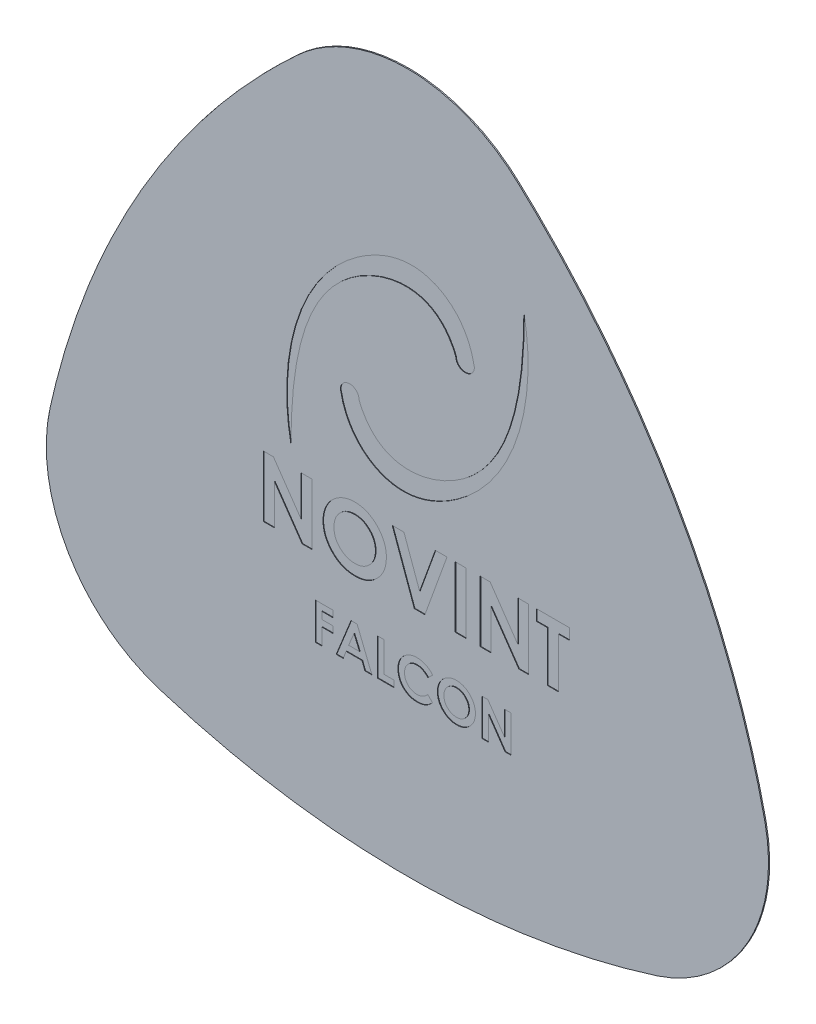
SolidWorks part; units mm, degrees
ref_plane "Plan de face" through (0, 0, 0) normal (0, 0, 1) x (1, 0, 0)
ref_plane "Plan de dessus" through (0, 0, 0) normal (0, 1, 0) x (1, 0, 0)
ref_plane "Plan de droite" through (0, 0, 0) normal (1, 0, 0) x (0, 0, -1)
sketch "Esquisse1" plane through (0, 0, 0) normal (0, 0, 1) x (1, 0, 0)
  spline S1 degree 3 poles (0, 149.25) (-0.1919, 149.25) (-0.4824, 149.2433) (-0.8671, 149.2249) (-1.227, 149.1976) (-1.4757, 149.1726) (-2.3358, 149.0732) (-3.7825, 148.7898) (-5.8615, 148.0277) (-7.7866, 146.9536) (-8.9312, 146.0552) (-11.3317, 143.854) (-14.9023, 140.2132) (-19.6452, 134.2118) (-23.6946, 127.7866) (-25.8978, 123.3061) (-27.3362, 119.9581) (-28.1637, 117.8887) (-29.2237, 114.8517) (-30.1569, 111.7368) (-30.7179, 109.4995) (-31.1222, 107.6788) (-31.3307, 106.3612) (-31.3402, 104.0862) (-30.9316, 101.6832) (-30.3995, 100.201) (-29.6911, 98.6209) (-28.6528, 96.8267) (-26.4804, 94.5101) (-23.992, 92.8324) (-22.3292, 92.1495) (-18.9808, 91.0951) (-13.9201, 89.8123) (-6.4025, 88.7423) (1.0481, 88.4673) (5.9721, 88.7938) (9.5908, 89.2221) (11.7967, 89.5402) (14.9568, 90.1407) (18.121, 90.89) (20.339, 91.5228) (22.118, 92.083) (23.3633, 92.5612) (25.3382, 93.6905) (27.215, 95.2458) (28.2326, 96.4478) (29.2467, 97.8513) (30.2814, 99.6476) (31.2015, 102.6873) (31.4102, 105.6811) (31.1702, 107.4626) (30.4092, 110.8896) (28.9898, 115.9137) (26.1576, 122.9592) (22.6705, 129.5491) (19.9257, 133.6501) (17.7454, 136.5698) (16.3935, 138.2864) (14.353, 140.661) (12.1535, 143.0027) (10.4653, 144.6485) (9.0029, 145.9895) (8.1968, 146.6474) (6.7793, 147.5233) (5.532, 148.1378) (4.1307, 148.6556) (2.6685, 149.0197) (1.2601, 149.2151) (0.4041, 149.25) (0, 149.25) (-0.1919, 149.25) (-0.4824, 149.2433) knots -0.004472 0 0 0 0.002123 0.004246 0.006369 0.008493 0.008493 0.020144 0.031796 0.043448 0.0551 0.0551 0.096159 0.137217 0.178275 0.219334 0.219334 0.238889 0.258444 0.277999 0.297554 0.297554 0.307313 0.317071 0.326829 0.336587 0.336587 0.349549 0.36251 0.375472 0.388433 0.388433 0.429492 0.47055 0.511609 0.552667 0.552667 0.572222 0.591777 0.611333 0.630888 0.630888 0.640646 0.650404 0.660162 0.66992 0.66992 0.682882 0.695844 0.708805 0.721767 0.721767 0.762825 0.803884 0.844942 0.886 0.886 0.905556 0.925111 0.944666 0.964221 0.964221 0.973166 0.977638 0.982111 0.986583 0.991055 0.995528 1 1 1 1.002123 1.004246 1.006369 only from (0, 149.25) to (0, 149.25)
extrude "Boss.-Extru.1" add sketch "Esquisse1" along normal blind 0.1
sketch "Esquisse2" plane through (0, 0, 0.1) normal (0, 0, 1) x (1, 0, 0)
  line L0 (-13.0847, 108.9955) -> (14.3157, 108.9955) construction
  line L1 (-8.3489, 102.1759) -> (11.1625, 102.1759) construction
  line L2 (0, 149.25) -> (0, 107.1447) construction
  arc A0 (4.1921, 129.7302) -> (5.8103, 129.7302) centre (5.0012, 129.7302) ccw
  arc A1 (-4.1921, 122.2698) -> (-5.8103, 122.2698) centre (-5.0012, 122.2698) ccw
  spline S0 degree 3 poles (0, 149.25) (-0.1919, 149.25) (-0.4824, 149.2433) (-0.8671, 149.2249) (-1.227, 149.1976) (-1.4757, 149.1726) (-2.3358, 149.0732) (-3.7825, 148.7898) (-5.8615, 148.0277) (-7.7866, 146.9536) (-8.9312, 146.0552) (-11.3317, 143.854) (-14.9023, 140.2132) (-19.6452, 134.2118) (-23.6946, 127.7866) (-25.8978, 123.3061) (-27.3362, 119.9581) (-28.1637, 117.8887) (-29.2237, 114.8517) (-30.1569, 111.7368) (-30.7179, 109.4995) (-31.1222, 107.6788) (-31.3307, 106.3612) (-31.3402, 104.0862) (-30.9316, 101.6832) (-30.3995, 100.201) (-29.6911, 98.6209) (-28.6528, 96.8267) (-26.4804, 94.5101) (-23.992, 92.8324) (-22.3292, 92.1495) (-18.9808, 91.0951) (-13.9201, 89.8123) (-6.4025, 88.7423) (1.0481, 88.4673) (5.9721, 88.7938) (9.5908, 89.2221) (11.7967, 89.5402) (14.9568, 90.1407) (18.121, 90.89) (20.339, 91.5228) (22.118, 92.083) (23.3633, 92.5612) (25.3382, 93.6905) (27.215, 95.2458) (28.2326, 96.4478) (29.2467, 97.8513) (30.2814, 99.6476) (31.2015, 102.6873) (31.4102, 105.6811) (31.1702, 107.4626) (30.4092, 110.8896) (28.9898, 115.9137) (26.1576, 122.9592) (22.6705, 129.5491) (19.9257, 133.6501) (17.7454, 136.5698) (16.3935, 138.2864) (14.353, 140.661) (12.1535, 143.0027) (10.4653, 144.6485) (9.0029, 145.9895) (8.1968, 146.6474) (6.7793, 147.5233) (5.532, 148.1378) (4.1307, 148.6556) (2.6685, 149.0197) (1.2601, 149.2151) (0.4041, 149.25) (0, 149.25) (-0.1919, 149.25) (-0.4824, 149.2433) knots -0.004472 0 0 0 0.002123 0.004246 0.006369 0.008493 0.008493 0.020144 0.031796 0.043448 0.0551 0.0551 0.096159 0.137217 0.178275 0.219334 0.219334 0.238889 0.258444 0.277999 0.297554 0.297554 0.307313 0.317071 0.326829 0.336587 0.336587 0.349549 0.36251 0.375472 0.388433 0.388433 0.429492 0.47055 0.511609 0.552667 0.552667 0.572222 0.591777 0.611333 0.630888 0.630888 0.640646 0.650404 0.660162 0.66992 0.66992 0.682882 0.695844 0.708805 0.721767 0.721767 0.762825 0.803884 0.844942 0.886 0.886 0.905556 0.925111 0.944666 0.964221 0.964221 0.973166 0.977638 0.982111 0.986583 0.991055 0.995528 1 1 1 1.002123 1.004246 1.006369 only from (0, 149.25) to (0, 149.25) construction
  spline S1 degree 3 poles (5.8103, 129.7302) (5.2488, 132.8748) (1.2024, 135.8625) (-9.144, 131.0676) (-11.2806, 122.0656) (-10.1022, 115.9753) knots 0 0 0 0 0.231488 0.407412 1 1 1 1
  spline S2 degree 3 poles (-10.1022, 115.9753) (-10.0825, 120.897) (-9.1558, 131.8365) (2.4226, 134.1417) (4.1921, 129.7302) knots 0 0 0 0 0.598513 1 1 1 1
  spline S3 degree 3 poles (10.1022, 136.0247) (10.0825, 131.103) (9.1558, 120.1635) (-2.4226, 117.8583) (-4.1921, 122.2698) knots 0 0 0 0 0.598513 1 1 1 1
  spline S4 degree 3 poles (-5.8103, 122.2698) (-5.2488, 119.1252) (-1.2024, 116.1375) (9.144, 120.9324) (11.2806, 129.9344) (10.1022, 136.0247) knots 0 0 0 0 0.231488 0.407412 1 1 1 1
  text T0 "<b>FALCON</b>" font "Century Gothic" height in points 12
  text T1 "<b>NOVINT</b>" font "Century Gothic" height in points 20
  point P17 (-1.3064, 127.048)
  dimension "D1" = 2
extrude "Enlèv. mat.-Extru.1" cut sketch "Esquisse2" against normal blind 0.05
